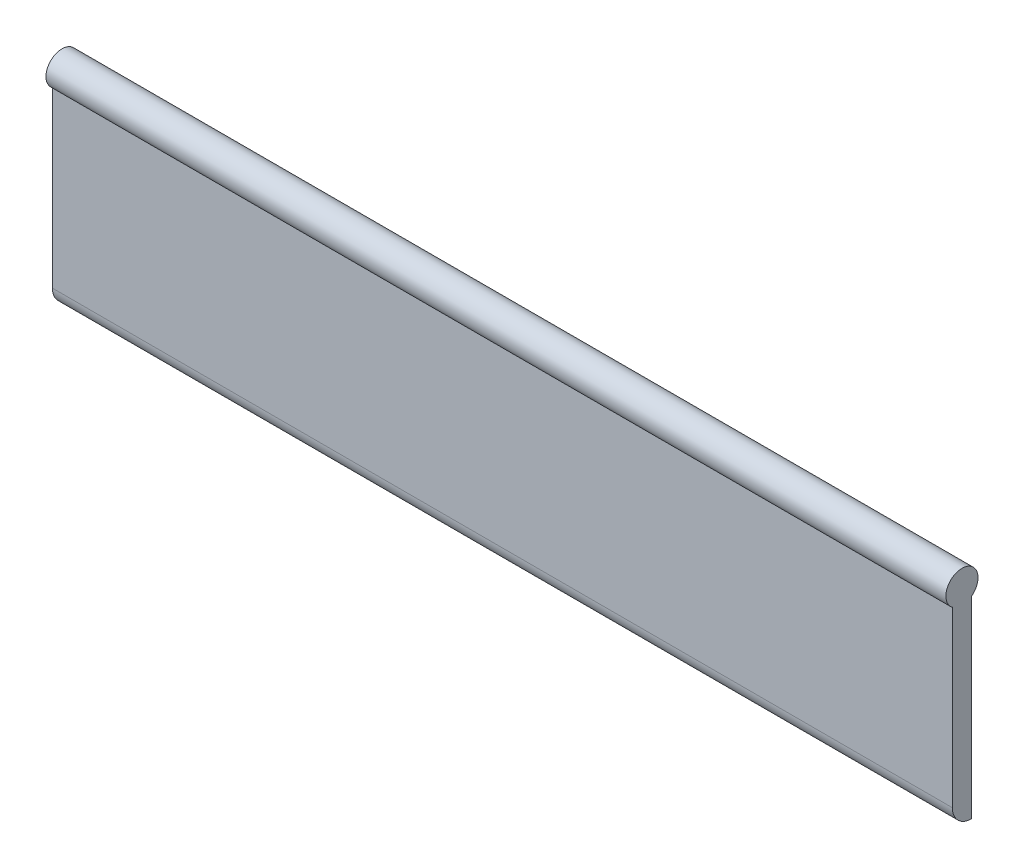
SolidWorks part; units mm, degrees
ref_plane "Front Plane" through (0, 0, 0) normal (0, 0, 1) x (1, 0, 0)
ref_plane "Top Plane" through (0, 0, 0) normal (0, 1, 0) x (1, 0, 0)
ref_plane "Right Plane" through (0, 0, 0) normal (1, 0, 0) x (0, 0, -1)
sketch "Sketch1" plane through (0, 0, 0) normal (1, 0, 0) x (0, 0, -1)
  line L1 (0, 0) -> (3, 0)
  line L2 (0, 0) -> (0, 32)
  line L3 (0, 32) -> (3, 32)
  line L4 (3, 0) -> (3, 32)
  circle A0 centre (1.5, 32) radius 2.5
  arc A1 (3, 0) -> (0, 3) centre (3, 3) cw
  point P9 (0, 0)
  point P10 (0, 2.7233)
  dimension "D1" = 5
  dimension "D2" = 3
  dimension "D3" = 32
extrude "Boss-Extrude1" add sketch "Sketch1" along normal blind 140 contours L4 A0 L2 L3 | L2 A0 L4 L3 | A0 L2 L1 L4
